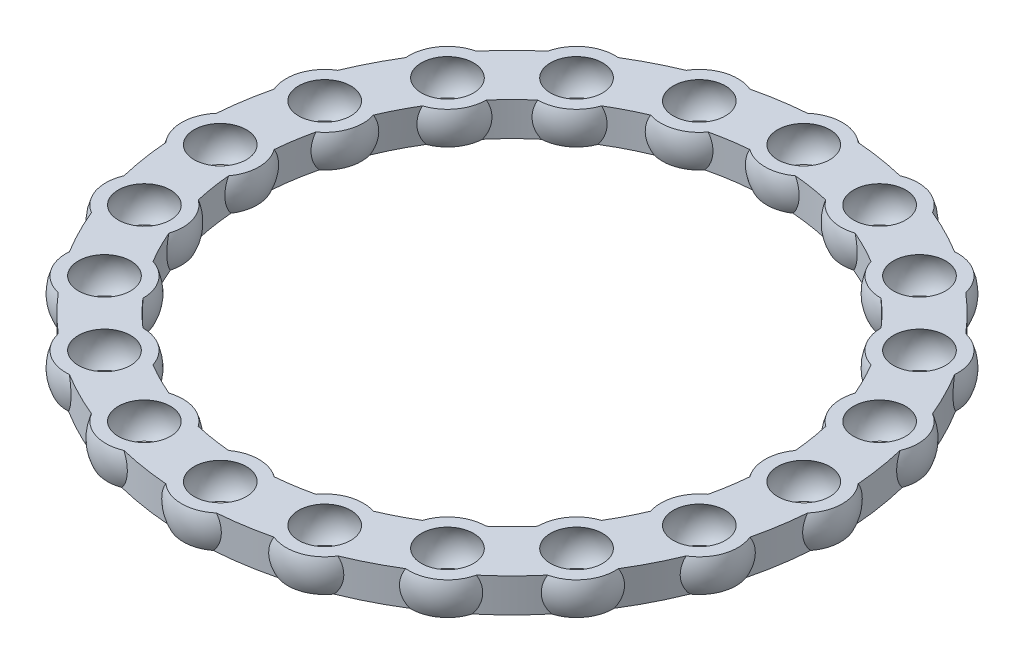
SolidWorks part; units mm, degrees
ref_plane "Front Plane" through (0, 0, 0) normal (0, 0, 1) x (1, 0, 0)
ref_plane "Top Plane" through (0, 0, 0) normal (0, 1, 0) x (1, 0, 0)
ref_plane "Right Plane" through (0, 0, 0) normal (1, 0, 0) x (0, 0, -1)
sketch "Sketch1" plane through (0, 0, 0) normal (0, 1, 0) x (1, 0, 0)
  circle A0 centre (0, 0) radius 42.75
  circle A1 centre (0, 0) radius 34.75
  circle A2 centre (0, 0) radius 38.75 construction
  circle A3 centre (0, 38.75) radius 4 construction
  dimension "D1" = 77.5
  dimension "D2" = 8
  dimension "D3" = 4
  dimension "D4" = 4
  dimension "D5" = 38.75
extrude "Boss-Extrude1" add sketch "Sketch1" along normal blind 2 and the other way blind 2.5
sketch "Sketch2" plane through (0, 0, 0) normal (0, 1, 0) x (1, 0, 0)
  line L0 (-5.5, 38.75) -> (5.5, 38.75)
  line L1 (0, 38.75) -> (0, 0) construction
  arc A0 (-5.5, 38.75) -> (5.5, 38.75) centre (0, 38.75) cw
  dimension "D2" = 5.5
  dimension "D1" = 38.75
revolve "Revolve1" add sketch "Sketch2" angle 360 about L0
pattern_circular "CirPattern1" count 20 over 360 about axis through (0, 0, 0) along (0, 1, 0) of "Revolve1"
sketch "Sketch3" plane through (0, 0, 0) normal (0, 0, 1) x (1, 0, 0)
  line L0 (-16.3653, 2) -> (-22.3317, 2) construction
  line L1 (-49.4692, 2) -> (46.907, 2)
  line L2 (-49.4692, 2) -> (-49.4692, 6.3516)
  line L3 (-49.4692, 6.3516) -> (46.907, 6.3516)
  line L4 (46.907, 2) -> (46.907, 6.3516)
  line L5 (-42.6468, -2.5) -> (-41.477, -2.5) construction
  line L6 (-49.4692, -2.5) -> (50.6187, -2.5)
  line L7 (-49.4692, -2.5) -> (-49.4692, -10.6783)
  line L8 (-49.4692, -10.6783) -> (50.6187, -10.6783)
  line L9 (50.6187, -2.5) -> (50.6187, -10.6783)
extrude "Cut-Extrude1" cut sketch "Sketch3" against normal through all both and the other way through all
sketch "Sketch4" plane through (0, 0, 0) normal (0, 1, 0) x (1, 0, 0)
  line L0 (0, 0) -> (0, 38.75) construction
  line L1 (-4, 38.75) -> (4, 38.75)
  arc A0 (-4, 38.75) -> (4, 38.75) centre (0, 38.75) cw
  dimension "D1" = 4
  dimension "D2" = 38.75
revolve "Cut-Revolve1" cut sketch "Sketch4" angle 360 about L1
pattern_circular "CirPattern2" count 20 over 360 about axis through (0, 0, 0) along (0, 1, 0) of "Cut-Revolve1"
